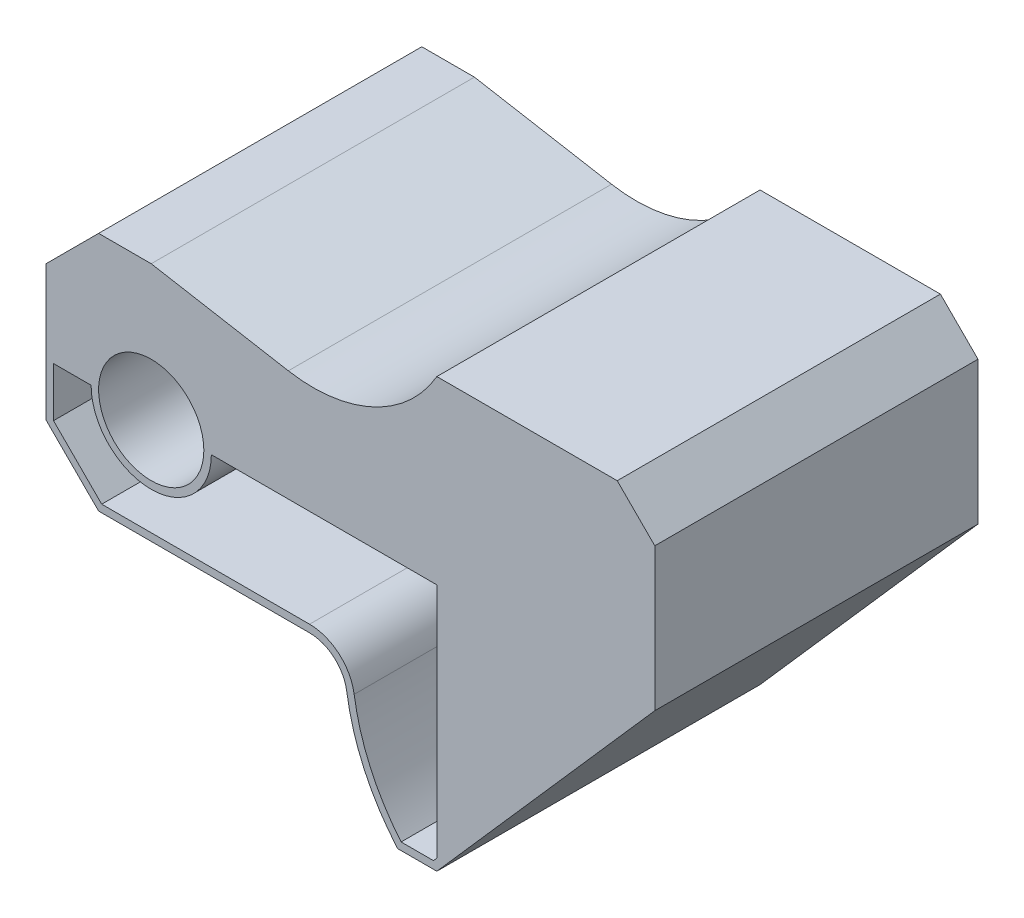
SolidWorks part; units mm, degrees
material "AISI 1020"
ref_plane "Front Plane" through (0, 0, 0) normal (0, 0, 1) x (1, 0, 0)
ref_plane "Top Plane" through (0, 0, 0) normal (0, 1, 0) x (1, 0, 0)
ref_plane "Right Plane" through (0, 0, 0) normal (1, 0, 0) x (0, 0, -1)
sketch "Sketch1" plane through (0, 0, 0) normal (0, 0, 1) x (1, 0, 0)
  line L0 (-14, -7) -> (-14, 11)
  line L1 (-14, 11) -> (-7, 18)
  line L2 (-7, 18) -> (0, 18)
  line L3 (0, 18) -> (18.2431, 14.7833)
  line L4 (38, 24) -> (62, 24)
  line L5 (62, 24) -> (67, 19)
  line L6 (67, 19) -> (67, 0)
  line L7 (67, 0) -> (38, -33)
  line L8 (38, -33) -> (32.7881, -33)
  line L9 (-14, -7) -> (-7, -14)
  line L10 (-7, -14) -> (21.0666, -14)
  circle A0 centre (0, 0) radius 7
  arc A1 (18.2431, 14.7833) -> (38, 24) centre (21.5424, 33.4946) ccw
  arc A2 (21.0666, -14) -> (26.0123, -18.2647) centre (21.0666, -19) cw
  arc A3 (26.0123, -18.2647) -> (32.7881, -33) centre (54.697, -14) ccw
  dimension "D2" = 14
  dimension "D8" = 5
  dimension "D9" = 29
  dimension "D17" = 19
  dimension "D1" = 32
  dimension "D3" = 14
  dimension "D4" = 7
  dimension "D5" = 14
  dimension "D6" = 45
  dimension "D7" = 29
  dimension "D10" = 81
  dimension "D11" = 57
  dimension "D12" = 10
  dimension "D13" = 19
  dimension "D14" = 14
  dimension "D15" = 45
  dimension "D16" = 7
  dimension "D18" = 5
  dimension "D19" = 24
  dimension "D20" = 19
  dimension "D21" = 29
extrude "Boss-Extrude1" add sketch "Sketch1" along normal blind 43
sketch "Sketch2" plane through (0, 0, 43) normal (0, 0, 1) x (1, 0, 0)
  line L22 (8, 0) -> (38, 0)
  line L23 (-8, 0) -> (-13, 0)
  line L24 (38, 0) -> (38, -31.4851)
  line L25 (38, 24) -> (38, 0) construction
  line L33 (-13, -6.5858) -> (-6.5858, -13)
  line L34 (-6.5858, -13) -> (21.0666, -13)
  line L35 (37.5475, -32) -> (66, 0.377)
  line L36 (66, 0.377) -> (66, 18.5858)
  line L37 (61.5858, 23) -> (38.5678, 23)
  line L38 (18.0694, 13.7984) -> (-0.0875, 17)
  line L39 (-0.0875, 17) -> (-6.5858, 17)
  line L40 (-6.5858, 17) -> (-13, 10.5858)
  line L41 (-13, 10.5858) -> (-13, -6.5858)
  line L42 (-13, -6.5858) -> (-6.5858, -13)
  line L43 (-6.5858, -13) -> (21.0666, -13)
  line L44 (37.5475, -32) -> (38, -31.4851)
  line L45 (-8, 0) -> (8, 0) construction
  line L46 (8, 0) -> (7.8431, -0.062) construction
  line L50 (-13, 0) -> (-13, -6.5858)
  line L51 (33.2494, -32) -> (37.5475, -32)
  line L52 (33.2494, -32) -> (37.5475, -32)
  line L53 (66, 18.5858) -> (61.5858, 23)
  circle A9 centre (0, 0) radius 8
  arc A10 (27.0014, -18.1176) -> (21.0666, -13) centre (21.0666, -19) ccw
  arc A11 (27.0014, -18.1176) -> (33.2494, -32) centre (54.697, -14) ccw
  arc A12 (18.0694, 13.7984) -> (38.5678, 23) centre (21.5424, 33.4946) ccw
  arc A13 (27.0014, -18.1176) -> (21.0666, -13) centre (21.0666, -19) ccw
  arc A14 (27.0014, -18.1176) -> (33.2494, -32) centre (54.697, -14) ccw
  arc A16 (-8, 0) -> (8, 0) centre (0, 0) ccw
  dimension "D1" = 1
  dimension "D2" = 1
extrude "Cut-Extrude1" cut sketch "Sketch2" against normal offset from surface (42 mm away) 1 up to face at (23.5218, 0.4885, 0)
equation "\"A\"=81"
equation "\"D10@Sketch1\"=\"A\""
equation "\"B\"=57"
equation "\"D11@Sketch1\"=\"B\""
equation "\"C\"=43"
equation "\"D1@Boss-Extrude1\"=\"C\""
